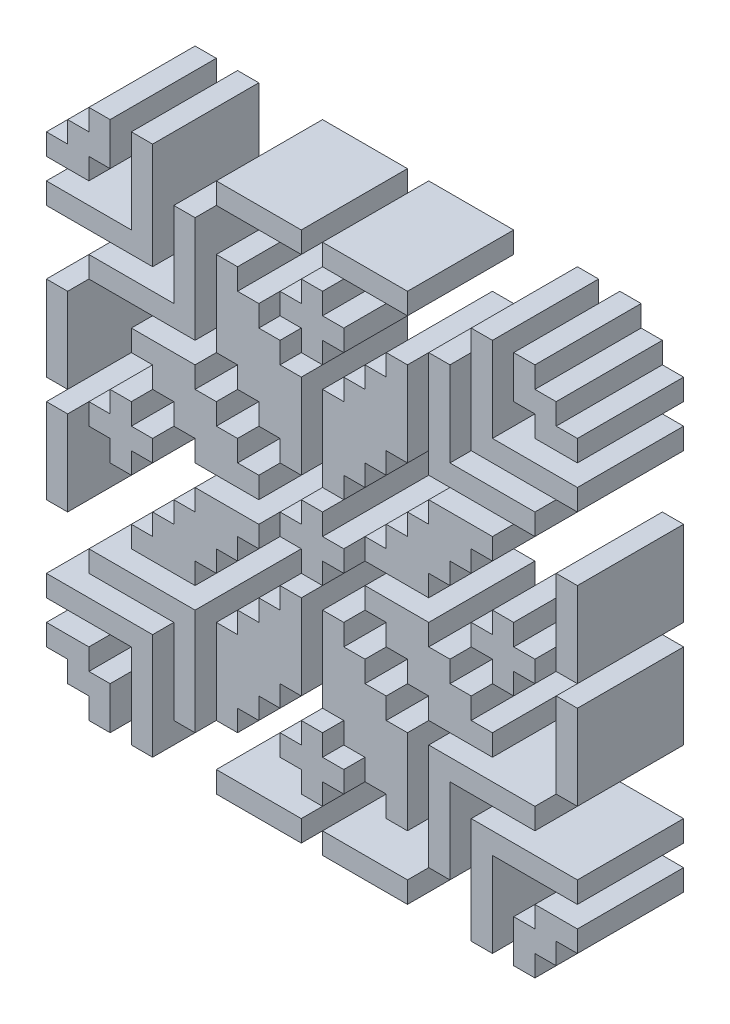
SolidWorks part; units mm, degrees
ref_plane "Спереди" through (0, 0, 0) normal (0, 0, 1) x (1, 0, 0)
ref_plane "Сверху" through (0, 0, 0) normal (0, 1, 0) x (1, 0, 0)
ref_plane "Справа" through (0, 0, 0) normal (1, 0, 0) x (0, 0, -1)
sketch "Эскиз1" plane through (0, 0, 0) normal (0, 0, 1) x (1, 0, 0)
  line L1 (-13.5, 13.5) -> (13.5, 13.5)
  line L2 (-13.5, 13.5) -> (-13.5, -13.5)
  line L3 (-13.5, -13.5) -> (13.5, -13.5)
  line L4 (13.5, 13.5) -> (13.5, -13.5)
  line L5 (-13.5, 13.5) -> (13.5, -13.5) construction
  line L6 (-13.5, -13.5) -> (13.5, 13.5) construction
  point P0 (0, 0)
  dimension "D1" = 27
  dimension "D2" = 27
extrude "Бобышка-Вытянуть1" [suppressed] add sketch "Эскиз1" along normal blind 3
sketch "Эскиз2" [suppressed] plane through (0, 0, 0) normal (0, 0, 1) x (1, 0, 0)
  line L0 (0, 0) -> (-13.5, 0) construction
  line L1 (-13.5, 13.5) -> (-13.5, -13.5) construction
  line L2 (0, 0) -> (0, -13.5) construction
  line L3 (-13.5, -13.5) -> (13.5, -13.5) construction
  line L4 (-0.5, -0.5) -> (-1.5, -0.5)
  line L5 (0.5, -1.5) -> (-0.5, -1.5)
  line L6 (0.5, -1.5) -> (0.5, -0.5)
  line L7 (0.5, 1.5) -> (-0.5, 1.5)
  line L8 (-0.5, -1.5) -> (-0.5, -0.5)
  line L9 (0.5, -1.5) -> (-0.5, 1.5) construction
  line L10 (0.5, 1.5) -> (-0.5, -1.5) construction
  line L11 (1.5, -0.5) -> (0.5, -0.5)
  line L12 (1.5, -0.5) -> (1.5, 0.5)
  line L13 (1.5, 0.5) -> (0.5, 0.5)
  line L14 (-1.5, -0.5) -> (-1.5, 0.5)
  line L15 (1.5, -0.5) -> (-1.5, 0.5) construction
  line L16 (1.5, 0.5) -> (-1.5, -0.5) construction
  line L17 (0.5, 0.5) -> (0.5, 1.5)
  line L18 (-0.5, 0.5) -> (-1.5, 0.5)
  line L19 (-0.5, 0.5) -> (-0.5, 1.5)
  line L20 (0, -9) -> (3.8771, -9) construction
  line L21 (1.5, 8.5) -> (-1.5, 9.5) construction
  line L22 (-0.5, -9.5) -> (-1.5, -9.5)
  line L23 (0.5, -10.5) -> (-0.5, -10.5)
  line L24 (0.5, -10.5) -> (0.5, -9.5)
  line L25 (0.5, -7.5) -> (-0.5, -7.5)
  line L26 (-0.5, -10.5) -> (-0.5, -9.5)
  line L27 (0.5, -10.5) -> (-0.5, -7.5) construction
  line L28 (0.5, -7.5) -> (-0.5, -10.5) construction
  line L29 (1.5, -9.5) -> (0.5, -9.5)
  line L30 (1.5, -9.5) -> (1.5, -8.5)
  line L31 (1.5, -8.5) -> (0.5, -8.5)
  line L32 (-1.5, -9.5) -> (-1.5, -8.5)
  line L33 (1.5, -9.5) -> (-1.5, -8.5) construction
  line L34 (1.5, -8.5) -> (-1.5, -9.5) construction
  line L35 (0.5, -8.5) -> (0.5, -7.5)
  line L36 (-0.5, -8.5) -> (-1.5, -8.5)
  line L37 (-0.5, -8.5) -> (-0.5, -7.5)
  line L38 (1.5, 9.5) -> (-1.5, 8.5) construction
  line L39 (0.5, 7.5) -> (-0.5, 10.5) construction
  line L40 (0.5, 10.5) -> (-0.5, 7.5) construction
  line L41 (-0.5, 8.5) -> (-0.5, 7.5)
  line L42 (-0.5, 8.5) -> (-1.5, 8.5)
  line L43 (0.5, 8.5) -> (0.5, 7.5)
  line L44 (-1.5, 9.5) -> (-1.5, 8.5)
  line L45 (1.5, 8.5) -> (0.5, 8.5)
  line L46 (1.5, 9.5) -> (1.5, 8.5)
  line L47 (1.5, 9.5) -> (0.5, 9.5)
  line L48 (-0.5, 10.5) -> (-0.5, 9.5)
  line L49 (0.5, 7.5) -> (-0.5, 7.5)
  line L50 (0.5, 10.5) -> (0.5, 9.5)
  line L51 (0.5, 10.5) -> (-0.5, 10.5)
  line L52 (-0.5, 9.5) -> (-1.5, 9.5)
  line L53 (2.5, -0.5) -> (5.5, -0.5)
  line L54 (5.5, -0.5) -> (5.5, -1.5)
  line L55 (5.5, -1.5) -> (6.5, -1.5)
  line L56 (6.5, -1.5) -> (6.5, -2.5)
  line L57 (6.5, -2.5) -> (7.5, -2.5)
  line L58 (7.5, -2.5) -> (7.5, -3.5)
  line L59 (7.5, -3.5) -> (8.5, -3.5)
  line L60 (8.5, -3.5) -> (8.5, -4.5)
  line L61 (8.5, -4.5) -> (5.5, -4.5)
  line L62 (5.5, -4.5) -> (5.5, -3.5)
  line L63 (5.5, -3.5) -> (4.5, -3.5)
  line L64 (4.5, -3.5) -> (4.5, -2.5)
  line L65 (4.5, -2.5) -> (3.5, -2.5)
  line L66 (3.5, -2.5) -> (3.5, -1.5)
  line L67 (3.5, -1.5) -> (2.5, -1.5)
  line L68 (2.5, -1.5) -> (2.5, -0.5)
  line L69 (5.5, -1.5) -> (5.5, -3.5) construction
  line L70 (5.5, -10.5) -> (5.5, -5.5)
  line L71 (5.5, -5.5) -> (10.5, -5.5)
  line L72 (10.5, -5.5) -> (10.5, -6.5)
  line L73 (10.5, -6.5) -> (6.5, -6.5)
  line L74 (6.5, -6.5) -> (6.5, -10.5)
  line L75 (6.5, -10.5) -> (5.5, -10.5)
  line L76 (5.5, -4.5) -> (5.5, -5.5) construction
  line L77 (8.5, -12.5) -> (7.5, -12.5)
  line L78 (7.5, -12.5) -> (7.5, -7.5)
  line L79 (7.5, -7.5) -> (12.5, -7.5)
  line L80 (12.5, -7.5) -> (12.5, -8.5)
  line L81 (12.5, -8.5) -> (8.5, -8.5)
  line L82 (8.5, -8.5) -> (8.5, -12.5)
  line L83 (9.5, -12.5) -> (9.5, -10.5)
  line L84 (9.5, -10.5) -> (10.5, -10.5)
  line L85 (10.5, -10.5) -> (10.5, -9.5)
  line L86 (10.5, -9.5) -> (12.5, -9.5)
  line L87 (12.5, -9.5) -> (12.5, -10.5)
  line L88 (12.5, -10.5) -> (11.5, -10.5)
  line L89 (11.5, -10.5) -> (11.5, -11.5)
  line L90 (11.5, -11.5) -> (10.5, -11.5)
  line L91 (10.5, -11.5) -> (10.5, -12.5)
  line L92 (10.5, -12.5) -> (9.5, -12.5)
  line L93 (0.5, -2.5) -> (0.5, -6.5)
  line L94 (0.5, -6.5) -> (1.5, -6.5)
  line L95 (1.5, -6.5) -> (1.5, -7.5)
  line L96 (1.5, -7.5) -> (2.5, -7.5)
  line L97 (2.5, -7.5) -> (2.5, -8.5)
  line L98 (2.5, -8.5) -> (3.5, -8.5)
  line L99 (3.5, -8.5) -> (3.5, -9.5)
  line L100 (3.5, -9.5) -> (4.5, -9.5)
  line L103 (4.5, -9.5) -> (4.5, -5.5)
  line L106 (4.5, -5.5) -> (3.5, -5.5)
  line L107 (3.5, -5.5) -> (3.5, -4.5)
  line L108 (3.5, -4.5) -> (2.5, -4.5)
  line L109 (2.5, -4.5) -> (2.5, -3.5)
  line L110 (2.5, -3.5) -> (1.5, -3.5)
  line L111 (1.5, -3.5) -> (1.5, -2.5)
  line L112 (1.5, -2.5) -> (0.5, -2.5)
  line L113 (0.5, -6.5) -> (0.5, -7.5) construction
  line L114 (1.5, -3.5) -> (1.5, -6.5) construction
  line L115 (2.5, -4.5) -> (2.5, -7.5) construction
  line L116 (0.5, -10.5) -> (0.5, -11.5) construction
  line L117 (4.5, -12.5) -> (0.5, -12.5)
  line L118 (4.5, -12.5) -> (4.5, -11.5)
  line L119 (4.5, -11.5) -> (0.5, -11.5)
  line L120 (0.5, -12.5) -> (0.5, -11.5)
  line L121 (9, 0) -> (17.8062, 0) construction
  line L122 (9, 0) -> (9, -6.8908) construction
  line L123 (8.5, -0.5) -> (7.5, -0.5)
  line L124 (9.5, -1.5) -> (8.5, -1.5)
  line L125 (9.5, -1.5) -> (9.5, -0.5)
  line L126 (9.5, 1.5) -> (8.5, 1.5)
  line L127 (8.5, -1.5) -> (8.5, -0.5)
  line L128 (9.5, -1.5) -> (8.5, 1.5) construction
  line L129 (9.5, 1.5) -> (8.5, -1.5) construction
  line L130 (10.5, -0.5) -> (9.5, -0.5)
  line L131 (10.5, -0.5) -> (10.5, 0.5)
  line L132 (10.5, 0.5) -> (9.5, 0.5)
  line L133 (7.5, -0.5) -> (7.5, 0.5)
  line L134 (10.5, -0.5) -> (7.5, 0.5) construction
  line L135 (10.5, 0.5) -> (7.5, -0.5) construction
  line L136 (9.5, 0.5) -> (9.5, 1.5)
  line L137 (8.5, 0.5) -> (7.5, 0.5)
  line L138 (8.5, 0.5) -> (8.5, 1.5)
  line L139 (-9, 0) -> (0, 0) construction
  line L140 (-9, 0) -> (-9, -7.0023) construction
  line L141 (-9.5, -0.5) -> (-10.5, -0.5)
  line L142 (-8.5, -1.5) -> (-9.5, -1.5)
  line L143 (-8.5, -1.5) -> (-8.5, -0.5)
  line L144 (-8.5, 1.5) -> (-9.5, 1.5)
  line L145 (-9.5, -1.5) -> (-9.5, -0.5)
  line L146 (-8.5, -1.5) -> (-9.5, 1.5) construction
  line L147 (-8.5, 1.5) -> (-9.5, -1.5) construction
  line L148 (-7.5, -0.5) -> (-8.5, -0.5)
  line L149 (-7.5, -0.5) -> (-7.5, 0.5)
  line L150 (-7.5, 0.5) -> (-8.5, 0.5)
  line L151 (-10.5, -0.5) -> (-10.5, 0.5)
  line L152 (-7.5, -0.5) -> (-10.5, 0.5) construction
  line L153 (-7.5, 0.5) -> (-10.5, -0.5) construction
  line L154 (-8.5, 0.5) -> (-8.5, 1.5)
  line L155 (-9.5, 0.5) -> (-10.5, 0.5)
  line L156 (-9.5, 0.5) -> (-9.5, 1.5)
  line L157 (-4.5, -11.5) -> (-0.5, -11.5)
  line L158 (-0.5, -12.5) -> (-0.5, -11.5)
  line L159 (-4.5, -12.5) -> (-0.5, -12.5)
  line L160 (-4.5, -12.5) -> (-4.5, -11.5)
  line L161 (-10.5, -12.5) -> (-9.5, -12.5)
  line L162 (-10.5, -11.5) -> (-10.5, -12.5)
  line L163 (-11.5, -11.5) -> (-10.5, -11.5)
  line L164 (-11.5, -10.5) -> (-11.5, -11.5)
  line L165 (-12.5, -10.5) -> (-11.5, -10.5)
  line L166 (-12.5, -9.5) -> (-12.5, -10.5)
  line L167 (-10.5, -9.5) -> (-12.5, -9.5)
  line L168 (-10.5, -10.5) -> (-10.5, -9.5)
  line L169 (-9.5, -10.5) -> (-10.5, -10.5)
  line L170 (-9.5, -12.5) -> (-9.5, -10.5)
  line L171 (-12.5, -8.5) -> (-8.5, -8.5)
  line L172 (-12.5, -7.5) -> (-12.5, -8.5)
  line L173 (-7.5, -7.5) -> (-12.5, -7.5)
  line L174 (-7.5, -12.5) -> (-7.5, -7.5)
  line L175 (-8.5, -12.5) -> (-7.5, -12.5)
  line L176 (-8.5, -8.5) -> (-8.5, -12.5)
  line L177 (-6.5, -6.5) -> (-6.5, -10.5)
  line L178 (-10.5, -6.5) -> (-6.5, -6.5)
  line L179 (-10.5, -5.5) -> (-10.5, -6.5)
  line L180 (-5.5, -5.5) -> (-10.5, -5.5)
  line L181 (-5.5, -10.5) -> (-5.5, -5.5)
  line L182 (-6.5, -10.5) -> (-5.5, -10.5)
  line L183 (-3.5, -1.5) -> (-2.5, -1.5)
  line L184 (-3.5, -2.5) -> (-3.5, -1.5)
  line L185 (-4.5, -2.5) -> (-3.5, -2.5)
  line L186 (-4.5, -3.5) -> (-4.5, -2.5)
  line L187 (-5.5, -3.5) -> (-4.5, -3.5)
  line L188 (-5.5, -4.5) -> (-5.5, -3.5)
  line L189 (-8.5, -4.5) -> (-5.5, -4.5)
  line L190 (-8.5, -3.5) -> (-8.5, -4.5)
  line L191 (-7.5, -3.5) -> (-8.5, -3.5)
  line L192 (-7.5, -2.5) -> (-7.5, -3.5)
  line L193 (-6.5, -2.5) -> (-7.5, -2.5)
  line L194 (-6.5, -1.5) -> (-6.5, -2.5)
  line L195 (-5.5, -1.5) -> (-6.5, -1.5)
  line L196 (-5.5, -0.5) -> (-5.5, -1.5)
  line L197 (-2.5, -0.5) -> (-5.5, -0.5)
  line L198 (-2.5, -1.5) -> (-2.5, -0.5)
  line L199 (-3.5, -9.5) -> (-4.5, -9.5)
  line L200 (-3.5, -8.5) -> (-3.5, -9.5)
  line L201 (-2.5, -8.5) -> (-3.5, -8.5)
  line L202 (-2.5, -7.5) -> (-2.5, -8.5)
  line L203 (-1.5, -7.5) -> (-2.5, -7.5)
  line L204 (-1.5, -6.5) -> (-1.5, -7.5)
  line L205 (-0.5, -6.5) -> (-1.5, -6.5)
  line L206 (-0.5, -2.5) -> (-0.5, -6.5)
  line L207 (-1.5, -2.5) -> (-0.5, -2.5)
  line L208 (-1.5, -3.5) -> (-1.5, -2.5)
  line L209 (-2.5, -3.5) -> (-1.5, -3.5)
  line L210 (-2.5, -4.5) -> (-2.5, -3.5)
  line L211 (-3.5, -4.5) -> (-2.5, -4.5)
  line L212 (-3.5, -5.5) -> (-3.5, -4.5)
  line L213 (-4.5, -5.5) -> (-3.5, -5.5)
  line L214 (-4.5, -9.5) -> (-4.5, -5.5)
  line L215 (8.5, -4.5) -> (11.5, -4.5) construction
  line L216 (12.5, -0.5) -> (11.5, -0.5)
  line L217 (12.5, -0.5) -> (12.5, -4.5)
  line L218 (12.5, -4.5) -> (11.5, -4.5)
  line L219 (11.5, -0.5) -> (11.5, -4.5)
  line L220 (12.5, -4.5) -> (12.5, -7.5) construction
  line L221 (-12.5, -4.5) -> (-11.5, -4.5)
  line L222 (-11.5, -0.5) -> (-11.5, -4.5)
  line L223 (-12.5, -0.5) -> (-11.5, -0.5)
  line L224 (-12.5, -0.5) -> (-12.5, -4.5)
  line L225 (-10.5, 11.5) -> (-10.5, 12.5)
  line L226 (-11.5, 11.5) -> (-10.5, 11.5)
  line L227 (-11.5, 10.5) -> (-11.5, 11.5)
  line L228 (-12.5, 10.5) -> (-11.5, 10.5)
  line L229 (-12.5, 9.5) -> (-12.5, 10.5)
  line L230 (-10.5, 9.5) -> (-12.5, 9.5)
  line L231 (-10.5, 10.5) -> (-10.5, 9.5)
  line L232 (-9.5, 10.5) -> (-10.5, 10.5)
  line L233 (-9.5, 12.5) -> (-9.5, 10.5)
  line L234 (-10.5, 12.5) -> (-9.5, 12.5)
  line L235 (-12.5, 7.5) -> (-12.5, 8.5)
  line L236 (-7.5, 7.5) -> (-12.5, 7.5)
  line L237 (-7.5, 12.5) -> (-7.5, 7.5)
  line L238 (-8.5, 12.5) -> (-7.5, 12.5)
  line L239 (-8.5, 8.5) -> (-8.5, 12.5)
  line L240 (-12.5, 8.5) -> (-8.5, 8.5)
  line L241 (-10.5, 6.5) -> (-6.5, 6.5)
  line L242 (-10.5, 5.5) -> (-10.5, 6.5)
  line L243 (-5.5, 5.5) -> (-10.5, 5.5)
  line L244 (-5.5, 10.5) -> (-5.5, 5.5)
  line L245 (-6.5, 10.5) -> (-5.5, 10.5)
  line L246 (-6.5, 6.5) -> (-6.5, 10.5)
  line L247 (-12.5, 0.5) -> (-12.5, 4.5)
  line L248 (-12.5, 0.5) -> (-11.5, 0.5)
  line L249 (-11.5, 0.5) -> (-11.5, 4.5)
  line L250 (-12.5, 4.5) -> (-11.5, 4.5)
  line L251 (-3.5, 2.5) -> (-3.5, 1.5)
  line L252 (-4.5, 2.5) -> (-3.5, 2.5)
  line L253 (-4.5, 3.5) -> (-4.5, 2.5)
  line L254 (-5.5, 3.5) -> (-4.5, 3.5)
  line L255 (-5.5, 4.5) -> (-5.5, 3.5)
  line L256 (-8.5, 4.5) -> (-5.5, 4.5)
  line L257 (-8.5, 3.5) -> (-8.5, 4.5)
  line L258 (-7.5, 3.5) -> (-8.5, 3.5)
  line L259 (-7.5, 2.5) -> (-7.5, 3.5)
  line L260 (-6.5, 2.5) -> (-7.5, 2.5)
  line L261 (-6.5, 1.5) -> (-6.5, 2.5)
  line L262 (-5.5, 1.5) -> (-6.5, 1.5)
  line L263 (-5.5, 0.5) -> (-5.5, 1.5)
  line L264 (-2.5, 0.5) -> (-5.5, 0.5)
  line L265 (-2.5, 1.5) -> (-2.5, 0.5)
  line L266 (-3.5, 1.5) -> (-2.5, 1.5)
  line L267 (-3.5, 8.5) -> (-3.5, 9.5)
  line L268 (-2.5, 8.5) -> (-3.5, 8.5)
  line L269 (-2.5, 7.5) -> (-2.5, 8.5)
  line L270 (-1.5, 7.5) -> (-2.5, 7.5)
  line L271 (-1.5, 6.5) -> (-1.5, 7.5)
  line L272 (-0.5, 6.5) -> (-1.5, 6.5)
  line L273 (-0.5, 2.5) -> (-0.5, 6.5)
  line L274 (-1.5, 2.5) -> (-0.5, 2.5)
  line L275 (-1.5, 3.5) -> (-1.5, 2.5)
  line L276 (-2.5, 3.5) -> (-1.5, 3.5)
  line L277 (-2.5, 4.5) -> (-2.5, 3.5)
  line L278 (-3.5, 4.5) -> (-2.5, 4.5)
  line L279 (-3.5, 5.5) -> (-3.5, 4.5)
  line L280 (-4.5, 5.5) -> (-3.5, 5.5)
  line L281 (-4.5, 9.5) -> (-4.5, 5.5)
  line L282 (-3.5, 9.5) -> (-4.5, 9.5)
  line L283 (-4.5, 12.5) -> (-4.5, 11.5)
  line L284 (-4.5, 12.5) -> (-0.5, 12.5)
  line L285 (-0.5, 12.5) -> (-0.5, 11.5)
  line L286 (-4.5, 11.5) -> (-0.5, 11.5)
  line L287 (4.5, 11.5) -> (0.5, 11.5)
  line L288 (0.5, 12.5) -> (0.5, 11.5)
  line L289 (4.5, 12.5) -> (0.5, 12.5)
  line L290 (4.5, 12.5) -> (4.5, 11.5)
  line L291 (3.5, 9.5) -> (4.5, 9.5)
  line L292 (3.5, 8.5) -> (3.5, 9.5)
  line L293 (2.5, 8.5) -> (3.5, 8.5)
  line L294 (2.5, 7.5) -> (2.5, 8.5)
  line L295 (1.5, 7.5) -> (2.5, 7.5)
  line L296 (1.5, 6.5) -> (1.5, 7.5)
  line L297 (0.5, 6.5) -> (1.5, 6.5)
  line L298 (0.5, 2.5) -> (0.5, 6.5)
  line L299 (1.5, 2.5) -> (0.5, 2.5)
  line L300 (1.5, 3.5) -> (1.5, 2.5)
  line L301 (2.5, 3.5) -> (1.5, 3.5)
  line L302 (2.5, 4.5) -> (2.5, 3.5)
  line L303 (3.5, 4.5) -> (2.5, 4.5)
  line L304 (3.5, 5.5) -> (3.5, 4.5)
  line L305 (4.5, 5.5) -> (3.5, 5.5)
  line L306 (4.5, 9.5) -> (4.5, 5.5)
  line L307 (10.5, 12.5) -> (9.5, 12.5)
  line L308 (10.5, 11.5) -> (10.5, 12.5)
  line L309 (11.5, 11.5) -> (10.5, 11.5)
  line L310 (11.5, 10.5) -> (11.5, 11.5)
  line L311 (12.5, 10.5) -> (11.5, 10.5)
  line L312 (12.5, 9.5) -> (12.5, 10.5)
  line L313 (10.5, 9.5) -> (12.5, 9.5)
  line L314 (10.5, 10.5) -> (10.5, 9.5)
  line L315 (9.5, 10.5) -> (10.5, 10.5)
  line L316 (9.5, 12.5) -> (9.5, 10.5)
  line L317 (12.5, 8.5) -> (8.5, 8.5)
  line L318 (12.5, 7.5) -> (12.5, 8.5)
  line L319 (7.5, 7.5) -> (12.5, 7.5)
  line L320 (7.5, 12.5) -> (7.5, 7.5)
  line L321 (8.5, 12.5) -> (7.5, 12.5)
  line L322 (8.5, 8.5) -> (8.5, 12.5)
  line L323 (6.5, 6.5) -> (6.5, 10.5)
  line L324 (10.5, 6.5) -> (6.5, 6.5)
  line L325 (10.5, 5.5) -> (10.5, 6.5)
  line L326 (5.5, 5.5) -> (10.5, 5.5)
  line L327 (5.5, 10.5) -> (5.5, 5.5)
  line L328 (6.5, 10.5) -> (5.5, 10.5)
  line L329 (3.5, 1.5) -> (2.5, 1.5)
  line L330 (3.5, 2.5) -> (3.5, 1.5)
  line L331 (4.5, 2.5) -> (3.5, 2.5)
  line L332 (4.5, 3.5) -> (4.5, 2.5)
  line L333 (5.5, 3.5) -> (4.5, 3.5)
  line L334 (5.5, 4.5) -> (5.5, 3.5)
  line L335 (8.5, 4.5) -> (5.5, 4.5)
  line L336 (8.5, 3.5) -> (8.5, 4.5)
  line L337 (7.5, 3.5) -> (8.5, 3.5)
  line L338 (7.5, 2.5) -> (7.5, 3.5)
  line L339 (6.5, 2.5) -> (7.5, 2.5)
  line L340 (6.5, 1.5) -> (6.5, 2.5)
  line L341 (5.5, 1.5) -> (6.5, 1.5)
  line L342 (5.5, 0.5) -> (5.5, 1.5)
  line L343 (2.5, 0.5) -> (5.5, 0.5)
  line L344 (2.5, 1.5) -> (2.5, 0.5)
  line L345 (12.5, 4.5) -> (11.5, 4.5)
  line L346 (11.5, 0.5) -> (11.5, 4.5)
  line L347 (12.5, 0.5) -> (11.5, 0.5)
  line L348 (12.5, 0.5) -> (12.5, 4.5)
  point P65 (5.5, -1.5)
  dimension "D1" = 3
  dimension "D2" = 3
  dimension "D3" = 1
  dimension "D4" = 1
  dimension "D5" = 3
  dimension "D6" = 3
  dimension "D7" = 1
  dimension "D8" = 1
  dimension "D9" = 9
  dimension "D10" = 1
  dimension "D11" = 1
  dimension "D12" = 1
  dimension "D13" = 1
  dimension "D14" = 1
  dimension "D15" = 1
  dimension "D16" = 1
  dimension "D17" = 1
  dimension "D18" = 1
  dimension "D19" = 1
  dimension "D20" = 1
  dimension "D21" = 1
  dimension "D22" = 1
  dimension "D23" = 0.5
  dimension "D24" = 1
  dimension "D25" = 1
  dimension "D26" = 1
  dimension "D27" = 5
  dimension "D28" = 5
  dimension "D29" = 1
  dimension "D30" = 5
  dimension "D31" = 5
  dimension "D32" = 1
  dimension "D33" = 1
  dimension "D34" = 1
  dimension "D35" = 1
  dimension "D36" = 2
  dimension "D37" = 1
  dimension "D38" = 1
  dimension "D39" = 1
  dimension "D40" = 1
  dimension "D41" = 1
  dimension "D42" = 1
  dimension "D43" = 1
  dimension "D44" = 1
  dimension "D45" = 1
  dimension "D46" = 1
  dimension "D47" = 1
  dimension "D48" = 1
  dimension "D49" = 1
  dimension "D50" = 1
  dimension "D51" = 1
  dimension "D52" = 1
  dimension "D53" = 1
  dimension "D54" = 4
  dimension "D55" = 4
  dimension "D56" = 1
  dimension "D57" = 1
  dimension "D58" = 1
  dimension "D59" = 1
  dimension "D60" = 1
  dimension "D61" = 1
  dimension "D62" = 3
  dimension "D63" = 3
  dimension "D64" = 1
  dimension "D65" = 1
  dimension "D66" = 3
  dimension "D67" = 3
  dimension "D68" = 1
  dimension "D69" = 1
  dimension "D70" = 9
  dimension "D71" = 9
  dimension "D72" = 1
  dimension "D73" = 4
extrude "Бобышка-Вытянуть2" [suppressed] add sketch "Эскиз2" along normal blind 10
sketch "Эскиз3" plane through (0, 0, 0) normal (0, 0, 1) x (1, 0, 0)
  line L0 (0, 0) -> (0, 54.9561) construction
  line L1 (0, 0) -> (20.3527, 0) construction
  line L2 (0, 0) -> (0, -2.9834) construction
  line L3 (-0.5, -0.5) -> (-1.5, -0.5)
  line L4 (0.5, -1.5) -> (-0.5, -1.5)
  line L5 (0.5, -1.5) -> (0.5, -0.5)
  line L6 (0.5, 1.5) -> (-0.5, 1.5)
  line L7 (-0.5, -1.5) -> (-0.5, -0.5)
  line L8 (0.5, -1.5) -> (-0.5, 1.5) construction
  line L9 (0.5, 1.5) -> (-0.5, -1.5) construction
  line L10 (1.5, -0.5) -> (0.5, -0.5)
  line L11 (1.5, -0.5) -> (1.5, 0.5)
  line L12 (1.5, 0.5) -> (0.5, 0.5)
  line L13 (-1.5, -0.5) -> (-1.5, 0.5)
  line L14 (1.5, -0.5) -> (-1.5, 0.5) construction
  line L15 (1.5, 0.5) -> (-1.5, -0.5) construction
  line L16 (0.5, 0.5) -> (0.5, 1.5)
  line L17 (-0.5, 0.5) -> (-1.5, 0.5)
  line L18 (-0.5, 0.5) -> (-0.5, 1.5)
  line L19 (0, -9) -> (37.7298, -9) construction
  line L20 (1.5, 8.5) -> (-1.5, 9.5) construction
  line L21 (-0.5, -9.5) -> (-1.5, -9.5)
  line L22 (0.5, -10.5) -> (-0.5, -10.5)
  line L23 (0.5, -10.5) -> (0.5, -9.5)
  line L24 (0.5, -7.5) -> (-0.5, -7.5)
  line L25 (-0.5, -10.5) -> (-0.5, -9.5)
  line L26 (0.5, -10.5) -> (-0.5, -7.5) construction
  line L27 (0.5, -7.5) -> (-0.5, -10.5) construction
  line L28 (1.5, -9.5) -> (0.5, -9.5)
  line L29 (1.5, -9.5) -> (1.5, -8.5)
  line L30 (1.5, -8.5) -> (0.5, -8.5)
  line L31 (-1.5, -9.5) -> (-1.5, -8.5)
  line L32 (1.5, -9.5) -> (-1.5, -8.5) construction
  line L33 (1.5, -8.5) -> (-1.5, -9.5) construction
  line L34 (0.5, -8.5) -> (0.5, -7.5)
  line L35 (-0.5, -8.5) -> (-1.5, -8.5)
  line L36 (-0.5, -8.5) -> (-0.5, -7.5)
  line L37 (1.5, 9.5) -> (-1.5, 8.5) construction
  line L38 (0.5, 7.5) -> (-0.5, 10.5) construction
  line L39 (0.5, 10.5) -> (-0.5, 7.5) construction
  line L40 (-0.5, 8.5) -> (-0.5, 7.5)
  line L41 (-0.5, 8.5) -> (-1.5, 8.5)
  line L42 (0.5, 8.5) -> (0.5, 7.5)
  line L43 (-1.5, 9.5) -> (-1.5, 8.5)
  line L44 (1.5, 8.5) -> (0.5, 8.5)
  line L45 (1.5, 9.5) -> (1.5, 8.5)
  line L46 (1.5, 9.5) -> (0.5, 9.5)
  line L47 (-0.5, 10.5) -> (-0.5, 9.5)
  line L48 (0.5, 7.5) -> (-0.5, 7.5)
  line L49 (0.5, 10.5) -> (0.5, 9.5)
  line L50 (0.5, 10.5) -> (-0.5, 10.5)
  line L51 (-0.5, 9.5) -> (-1.5, 9.5)
  line L52 (2.5, -0.5) -> (5.5, -0.5)
  line L53 (5.5, -0.5) -> (5.5, -1.5)
  line L54 (5.5, -1.5) -> (6.5, -1.5)
  line L55 (6.5, -1.5) -> (6.5, -2.5)
  line L56 (6.5, -2.5) -> (7.5, -2.5)
  line L57 (7.5, -2.5) -> (7.5, -3.5)
  line L58 (7.5, -3.5) -> (8.5, -3.5)
  line L59 (8.5, -3.5) -> (8.5, -4.5)
  line L60 (8.5, -4.5) -> (5.5, -4.5)
  line L61 (5.5, -4.5) -> (5.5, -3.5)
  line L62 (5.5, -3.5) -> (4.5, -3.5)
  line L63 (4.5, -3.5) -> (4.5, -2.5)
  line L64 (4.5, -2.5) -> (3.5, -2.5)
  line L65 (3.5, -2.5) -> (3.5, -1.5)
  line L66 (3.5, -1.5) -> (2.5, -1.5)
  line L67 (2.5, -1.5) -> (2.5, -0.5)
  line L68 (5.5, -1.5) -> (5.5, -3.5) construction
  line L69 (5.5, -10.5) -> (5.5, -5.5)
  line L70 (5.5, -5.5) -> (10.5, -5.5)
  line L71 (10.5, -5.5) -> (10.5, -6.5)
  line L72 (10.5, -6.5) -> (6.5, -6.5)
  line L73 (6.5, -6.5) -> (6.5, -10.5)
  line L74 (6.5, -10.5) -> (5.5, -10.5)
  line L75 (5.5, -4.5) -> (5.5, -5.5) construction
  line L76 (8.5, -12.5) -> (7.5, -12.5)
  line L77 (7.5, -12.5) -> (7.5, -7.5)
  line L78 (7.5, -7.5) -> (12.5, -7.5)
  line L79 (12.5, -7.5) -> (12.5, -8.5)
  line L80 (12.5, -8.5) -> (8.5, -8.5)
  line L81 (8.5, -8.5) -> (8.5, -12.5)
  line L82 (9.5, -12.5) -> (9.5, -10.5)
  line L83 (9.5, -10.5) -> (10.5, -10.5)
  line L84 (10.5, -10.5) -> (10.5, -9.5)
  line L85 (10.5, -9.5) -> (12.5, -9.5)
  line L86 (12.5, -9.5) -> (12.5, -10.5)
  line L87 (12.5, -10.5) -> (11.5, -10.5)
  line L88 (11.5, -10.5) -> (11.5, -11.5)
  line L89 (11.5, -11.5) -> (10.5, -11.5)
  line L90 (10.5, -11.5) -> (10.5, -12.5)
  line L91 (10.5, -12.5) -> (9.5, -12.5)
  line L92 (0.5, -2.5) -> (0.5, -6.5)
  line L93 (0.5, -6.5) -> (1.5, -6.5)
  line L94 (1.5, -6.5) -> (1.5, -7.5)
  line L95 (1.5, -7.5) -> (2.5, -7.5)
  line L96 (2.5, -7.5) -> (2.5, -8.5)
  line L97 (2.5, -8.5) -> (3.5, -8.5)
  line L98 (3.5, -8.5) -> (3.5, -9.5)
  line L99 (3.5, -9.5) -> (4.5, -9.5)
  line L100 (4.5, -9.5) -> (4.5, -5.5)
  line L101 (4.5, -5.5) -> (3.5, -5.5)
  line L102 (3.5, -5.5) -> (3.5, -4.5)
  line L103 (3.5, -4.5) -> (2.5, -4.5)
  line L104 (2.5, -4.5) -> (2.5, -3.5)
  line L105 (2.5, -3.5) -> (1.5, -3.5)
  line L106 (1.5, -3.5) -> (1.5, -2.5)
  line L107 (1.5, -2.5) -> (0.5, -2.5)
  line L108 (0.5, -6.5) -> (0.5, -7.5) construction
  line L109 (1.5, -3.5) -> (1.5, -6.5) construction
  line L110 (2.5, -4.5) -> (2.5, -7.5) construction
  line L111 (0.5, -10.5) -> (0.5, -11.5) construction
  line L112 (4.5, -12.5) -> (0.5, -12.5)
  line L113 (4.5, -12.5) -> (4.5, -11.5)
  line L114 (4.5, -11.5) -> (0.5, -11.5)
  line L115 (0.5, -12.5) -> (0.5, -11.5)
  line L116 (9, 0) -> (51.6588, 0) construction
  line L117 (9, 0) -> (9, 3.6258) construction
  line L118 (8.5, -0.5) -> (7.5, -0.5)
  line L119 (9.5, -1.5) -> (8.5, -1.5)
  line L120 (9.5, -1.5) -> (9.5, -0.5)
  line L121 (9.5, 1.5) -> (8.5, 1.5)
  line L122 (8.5, -1.5) -> (8.5, -0.5)
  line L123 (9.5, -1.5) -> (8.5, 1.5) construction
  line L124 (9.5, 1.5) -> (8.5, -1.5) construction
  line L125 (10.5, -0.5) -> (9.5, -0.5)
  line L126 (10.5, -0.5) -> (10.5, 0.5)
  line L127 (10.5, 0.5) -> (9.5, 0.5)
  line L128 (7.5, -0.5) -> (7.5, 0.5)
  line L129 (10.5, -0.5) -> (7.5, 0.5) construction
  line L130 (10.5, 0.5) -> (7.5, -0.5) construction
  line L131 (9.5, 0.5) -> (9.5, 1.5)
  line L132 (8.5, 0.5) -> (7.5, 0.5)
  line L133 (8.5, 0.5) -> (8.5, 1.5)
  line L134 (-9, 0) -> (0, 0) construction
  line L135 (-9, 0) -> (-9, 3.5144) construction
  line L136 (-9.5, -0.5) -> (-10.5, -0.5)
  line L137 (-8.5, -1.5) -> (-9.5, -1.5)
  line L138 (-8.5, -1.5) -> (-8.5, -0.5)
  line L139 (-8.5, 1.5) -> (-9.5, 1.5)
  line L140 (-9.5, -1.5) -> (-9.5, -0.5)
  line L141 (-8.5, -1.5) -> (-9.5, 1.5) construction
  line L142 (-8.5, 1.5) -> (-9.5, -1.5) construction
  line L143 (-7.5, -0.5) -> (-8.5, -0.5)
  line L144 (-7.5, -0.5) -> (-7.5, 0.5)
  line L145 (-7.5, 0.5) -> (-8.5, 0.5)
  line L146 (-10.5, -0.5) -> (-10.5, 0.5)
  line L147 (-7.5, -0.5) -> (-10.5, 0.5) construction
  line L148 (-7.5, 0.5) -> (-10.5, -0.5) construction
  line L149 (-8.5, 0.5) -> (-8.5, 1.5)
  line L150 (-9.5, 0.5) -> (-10.5, 0.5)
  line L151 (-9.5, 0.5) -> (-9.5, 1.5)
  line L152 (-4.5, -11.5) -> (-0.5, -11.5)
  line L153 (-0.5, -12.5) -> (-0.5, -11.5)
  line L154 (-4.5, -12.5) -> (-0.5, -12.5)
  line L155 (-4.5, -12.5) -> (-4.5, -11.5)
  line L156 (-10.5, -12.5) -> (-9.5, -12.5)
  line L157 (-10.5, -11.5) -> (-10.5, -12.5)
  line L158 (-11.5, -11.5) -> (-10.5, -11.5)
  line L159 (-11.5, -10.5) -> (-11.5, -11.5)
  line L160 (-12.5, -10.5) -> (-11.5, -10.5)
  line L161 (-12.5, -9.5) -> (-12.5, -10.5)
  line L162 (-10.5, -9.5) -> (-12.5, -9.5)
  line L163 (-10.5, -10.5) -> (-10.5, -9.5)
  line L164 (-9.5, -10.5) -> (-10.5, -10.5)
  line L165 (-9.5, -12.5) -> (-9.5, -10.5)
  line L166 (-12.5, -8.5) -> (-8.5, -8.5)
  line L167 (-12.5, -7.5) -> (-12.5, -8.5)
  line L168 (-7.5, -7.5) -> (-12.5, -7.5)
  line L169 (-7.5, -12.5) -> (-7.5, -7.5)
  line L170 (-8.5, -12.5) -> (-7.5, -12.5)
  line L171 (-8.5, -8.5) -> (-8.5, -12.5)
  line L172 (-6.5, -6.5) -> (-6.5, -10.5)
  line L173 (-10.5, -6.5) -> (-6.5, -6.5)
  line L174 (-10.5, -5.5) -> (-10.5, -6.5)
  line L175 (-5.5, -5.5) -> (-10.5, -5.5)
  line L176 (-5.5, -10.5) -> (-5.5, -5.5)
  line L177 (-6.5, -10.5) -> (-5.5, -10.5)
  line L178 (-3.5, -1.5) -> (-2.5, -1.5)
  line L179 (-3.5, -2.5) -> (-3.5, -1.5)
  line L180 (-4.5, -2.5) -> (-3.5, -2.5)
  line L181 (-4.5, -3.5) -> (-4.5, -2.5)
  line L182 (-5.5, -3.5) -> (-4.5, -3.5)
  line L183 (-5.5, -4.5) -> (-5.5, -3.5)
  line L184 (-8.5, -4.5) -> (-5.5, -4.5)
  line L185 (-8.5, -3.5) -> (-8.5, -4.5)
  line L186 (-7.5, -3.5) -> (-8.5, -3.5)
  line L187 (-7.5, -2.5) -> (-7.5, -3.5)
  line L188 (-6.5, -2.5) -> (-7.5, -2.5)
  line L189 (-6.5, -1.5) -> (-6.5, -2.5)
  line L190 (-5.5, -1.5) -> (-6.5, -1.5)
  line L191 (-5.5, -0.5) -> (-5.5, -1.5)
  line L192 (-2.5, -0.5) -> (-5.5, -0.5)
  line L193 (-2.5, -1.5) -> (-2.5, -0.5)
  line L194 (-3.5, -9.5) -> (-4.5, -9.5)
  line L195 (-3.5, -8.5) -> (-3.5, -9.5)
  line L196 (-2.5, -8.5) -> (-3.5, -8.5)
  line L197 (-2.5, -7.5) -> (-2.5, -8.5)
  line L198 (-1.5, -7.5) -> (-2.5, -7.5)
  line L199 (-1.5, -6.5) -> (-1.5, -7.5)
  line L200 (-0.5, -6.5) -> (-1.5, -6.5)
  line L201 (-0.5, -2.5) -> (-0.5, -6.5)
  line L202 (-1.5, -2.5) -> (-0.5, -2.5)
  line L203 (-1.5, -3.5) -> (-1.5, -2.5)
  line L204 (-2.5, -3.5) -> (-1.5, -3.5)
  line L205 (-2.5, -4.5) -> (-2.5, -3.5)
  line L206 (-3.5, -4.5) -> (-2.5, -4.5)
  line L207 (-3.5, -5.5) -> (-3.5, -4.5)
  line L208 (-4.5, -5.5) -> (-3.5, -5.5)
  line L209 (-4.5, -9.5) -> (-4.5, -5.5)
  line L210 (8.5, -4.5) -> (11.5, -4.5) construction
  line L211 (12.5, -0.5) -> (11.5, -0.5)
  line L212 (12.5, -0.5) -> (12.5, -4.5)
  line L213 (12.5, -4.5) -> (11.5, -4.5)
  line L214 (11.5, -0.5) -> (11.5, -4.5)
  line L215 (12.5, -4.5) -> (12.5, -7.5) construction
  line L216 (-12.5, -4.5) -> (-11.5, -4.5)
  line L217 (-11.5, -0.5) -> (-11.5, -4.5)
  line L218 (-12.5, -0.5) -> (-11.5, -0.5)
  line L219 (-12.5, -0.5) -> (-12.5, -4.5)
  line L220 (-10.5, 11.5) -> (-10.5, 12.5)
  line L221 (-11.5, 11.5) -> (-10.5, 11.5)
  line L222 (-11.5, 10.5) -> (-11.5, 11.5)
  line L223 (-12.5, 10.5) -> (-11.5, 10.5)
  line L224 (-12.5, 9.5) -> (-12.5, 10.5)
  line L225 (-10.5, 9.5) -> (-12.5, 9.5)
  line L226 (-10.5, 10.5) -> (-10.5, 9.5)
  line L227 (-9.5, 10.5) -> (-10.5, 10.5)
  line L228 (-9.5, 12.5) -> (-9.5, 10.5)
  line L229 (-10.5, 12.5) -> (-9.5, 12.5)
  line L230 (-12.5, 7.5) -> (-12.5, 8.5)
  line L231 (-7.5, 7.5) -> (-12.5, 7.5)
  line L232 (-7.5, 12.5) -> (-7.5, 7.5)
  line L233 (-8.5, 12.5) -> (-7.5, 12.5)
  line L234 (-8.5, 8.5) -> (-8.5, 12.5)
  line L235 (-12.5, 8.5) -> (-8.5, 8.5)
  line L236 (-10.5, 6.5) -> (-6.5, 6.5)
  line L237 (-10.5, 5.5) -> (-10.5, 6.5)
  line L238 (-5.5, 5.5) -> (-10.5, 5.5)
  line L239 (-5.5, 10.5) -> (-5.5, 5.5)
  line L240 (-6.5, 10.5) -> (-5.5, 10.5)
  line L241 (-6.5, 6.5) -> (-6.5, 10.5)
  line L242 (-12.5, 0.5) -> (-12.5, 4.5)
  line L243 (-12.5, 0.5) -> (-11.5, 0.5)
  line L244 (-11.5, 0.5) -> (-11.5, 4.5)
  line L245 (-12.5, 4.5) -> (-11.5, 4.5)
  line L246 (-3.5, 2.5) -> (-3.5, 1.5)
  line L247 (-4.5, 2.5) -> (-3.5, 2.5)
  line L248 (-4.5, 3.5) -> (-4.5, 2.5)
  line L249 (-5.5, 3.5) -> (-4.5, 3.5)
  line L250 (-5.5, 4.5) -> (-5.5, 3.5)
  line L251 (-8.5, 4.5) -> (-5.5, 4.5)
  line L252 (-8.5, 3.5) -> (-8.5, 4.5)
  line L253 (-7.5, 3.5) -> (-8.5, 3.5)
  line L254 (-7.5, 2.5) -> (-7.5, 3.5)
  line L255 (-6.5, 2.5) -> (-7.5, 2.5)
  line L256 (-6.5, 1.5) -> (-6.5, 2.5)
  line L257 (-5.5, 1.5) -> (-6.5, 1.5)
  line L258 (-5.5, 0.5) -> (-5.5, 1.5)
  line L259 (-2.5, 0.5) -> (-5.5, 0.5)
  line L260 (-2.5, 1.5) -> (-2.5, 0.5)
  line L261 (-3.5, 1.5) -> (-2.5, 1.5)
  line L262 (-3.5, 8.5) -> (-3.5, 9.5)
  line L263 (-2.5, 8.5) -> (-3.5, 8.5)
  line L264 (-2.5, 7.5) -> (-2.5, 8.5)
  line L265 (-1.5, 7.5) -> (-2.5, 7.5)
  line L266 (-1.5, 6.5) -> (-1.5, 7.5)
  line L267 (-0.5, 6.5) -> (-1.5, 6.5)
  line L268 (-0.5, 2.5) -> (-0.5, 6.5)
  line L269 (-1.5, 2.5) -> (-0.5, 2.5)
  line L270 (-1.5, 3.5) -> (-1.5, 2.5)
  line L271 (-2.5, 3.5) -> (-1.5, 3.5)
  line L272 (-2.5, 4.5) -> (-2.5, 3.5)
  line L273 (-3.5, 4.5) -> (-2.5, 4.5)
  line L274 (-3.5, 5.5) -> (-3.5, 4.5)
  line L275 (-4.5, 5.5) -> (-3.5, 5.5)
  line L276 (-4.5, 9.5) -> (-4.5, 5.5)
  line L277 (-3.5, 9.5) -> (-4.5, 9.5)
  line L278 (-4.5, 12.5) -> (-4.5, 11.5)
  line L279 (-4.5, 12.5) -> (-0.5, 12.5)
  line L280 (-0.5, 12.5) -> (-0.5, 11.5)
  line L281 (-4.5, 11.5) -> (-0.5, 11.5)
  line L282 (4.5, 11.5) -> (0.5, 11.5)
  line L283 (0.5, 12.5) -> (0.5, 11.5)
  line L284 (4.5, 12.5) -> (0.5, 12.5)
  line L285 (4.5, 12.5) -> (4.5, 11.5)
  line L286 (3.5, 9.5) -> (4.5, 9.5)
  line L287 (3.5, 8.5) -> (3.5, 9.5)
  line L288 (2.5, 8.5) -> (3.5, 8.5)
  line L289 (2.5, 7.5) -> (2.5, 8.5)
  line L290 (1.5, 7.5) -> (2.5, 7.5)
  line L291 (1.5, 6.5) -> (1.5, 7.5)
  line L292 (0.5, 6.5) -> (1.5, 6.5)
  line L293 (0.5, 2.5) -> (0.5, 6.5)
  line L294 (1.5, 2.5) -> (0.5, 2.5)
  line L295 (1.5, 3.5) -> (1.5, 2.5)
  line L296 (2.5, 3.5) -> (1.5, 3.5)
  line L297 (2.5, 4.5) -> (2.5, 3.5)
  line L298 (3.5, 4.5) -> (2.5, 4.5)
  line L299 (3.5, 5.5) -> (3.5, 4.5)
  line L300 (4.5, 5.5) -> (3.5, 5.5)
  line L301 (4.5, 9.5) -> (4.5, 5.5)
  line L302 (10.5, 12.5) -> (9.5, 12.5)
  line L303 (10.5, 11.5) -> (10.5, 12.5)
  line L304 (11.5, 11.5) -> (10.5, 11.5)
  line L305 (11.5, 10.5) -> (11.5, 11.5)
  line L306 (12.5, 10.5) -> (11.5, 10.5)
  line L307 (12.5, 9.5) -> (12.5, 10.5)
  line L308 (10.5, 9.5) -> (12.5, 9.5)
  line L309 (10.5, 10.5) -> (10.5, 9.5)
  line L310 (9.5, 10.5) -> (10.5, 10.5)
  line L311 (9.5, 12.5) -> (9.5, 10.5)
  line L312 (12.5, 8.5) -> (8.5, 8.5)
  line L313 (12.5, 7.5) -> (12.5, 8.5)
  line L314 (7.5, 7.5) -> (12.5, 7.5)
  line L315 (7.5, 12.5) -> (7.5, 7.5)
  line L316 (8.5, 12.5) -> (7.5, 12.5)
  line L317 (8.5, 8.5) -> (8.5, 12.5)
  line L318 (6.5, 6.5) -> (6.5, 10.5)
  line L319 (10.5, 6.5) -> (6.5, 6.5)
  line L320 (10.5, 5.5) -> (10.5, 6.5)
  line L321 (5.5, 5.5) -> (10.5, 5.5)
  line L322 (5.5, 10.5) -> (5.5, 5.5)
  line L323 (6.5, 10.5) -> (5.5, 10.5)
  line L324 (3.5, 1.5) -> (2.5, 1.5)
  line L325 (3.5, 2.5) -> (3.5, 1.5)
  line L326 (4.5, 2.5) -> (3.5, 2.5)
  line L327 (4.5, 3.5) -> (4.5, 2.5)
  line L328 (5.5, 3.5) -> (4.5, 3.5)
  line L329 (5.5, 4.5) -> (5.5, 3.5)
  line L330 (8.5, 4.5) -> (5.5, 4.5)
  line L331 (8.5, 3.5) -> (8.5, 4.5)
  line L332 (7.5, 3.5) -> (8.5, 3.5)
  line L333 (7.5, 2.5) -> (7.5, 3.5)
  line L334 (6.5, 2.5) -> (7.5, 2.5)
  line L335 (6.5, 1.5) -> (6.5, 2.5)
  line L336 (5.5, 1.5) -> (6.5, 1.5)
  line L337 (5.5, 0.5) -> (5.5, 1.5)
  line L338 (2.5, 0.5) -> (5.5, 0.5)
  line L339 (2.5, 1.5) -> (2.5, 0.5)
  line L340 (12.5, 4.5) -> (11.5, 4.5)
  line L341 (11.5, 0.5) -> (11.5, 4.5)
  line L342 (12.5, 0.5) -> (11.5, 0.5)
  line L343 (12.5, 0.5) -> (12.5, 4.5)
  point P63 (5.5, -1.5)
  point P322 (0.4358, 0)
  point P323 (0, 0)
  dimension "D1" = 3
  dimension "D2" = 3
  dimension "D3" = 1
  dimension "D4" = 1
  dimension "D5" = 3
  dimension "D6" = 3
  dimension "D7" = 1
  dimension "D8" = 1
  dimension "D9" = 9
  dimension "D10" = 1
  dimension "D11" = 1
  dimension "D12" = 1
  dimension "D13" = 1
  dimension "D14" = 1
  dimension "D15" = 1
  dimension "D16" = 1
  dimension "D17" = 1
  dimension "D18" = 1
  dimension "D19" = 1
  dimension "D20" = 1
  dimension "D21" = 1
  dimension "D22" = 0.5
  dimension "D23" = 1
  dimension "D24" = 1
  dimension "D25" = 1
  dimension "D26" = 5
  dimension "D27" = 5
  dimension "D28" = 1
  dimension "D29" = 5
  dimension "D30" = 5
  dimension "D31" = 1
  dimension "D32" = 1
  dimension "D33" = 1
  dimension "D34" = 1
  dimension "D35" = 2
  dimension "D36" = 1
  dimension "D37" = 1
  dimension "D38" = 1
  dimension "D39" = 1
  dimension "D40" = 1
  dimension "D41" = 1
  dimension "D42" = 1
  dimension "D43" = 1
  dimension "D44" = 1
  dimension "D45" = 1
  dimension "D46" = 1
  dimension "D47" = 1
  dimension "D48" = 1
  dimension "D49" = 1
  dimension "D50" = 1
  dimension "D51" = 4
  dimension "D52" = 1
  dimension "D53" = 1
  dimension "D54" = 1
  dimension "D55" = 1
  dimension "D56" = 1
  dimension "D57" = 1
  dimension "D58" = 4
  dimension "D59" = 1
  dimension "D60" = 1
  dimension "D61" = 3
  dimension "D62" = 3
  dimension "D63" = 1
  dimension "D64" = 1
  dimension "D65" = 3
  dimension "D66" = 3
  dimension "D67" = 1
  dimension "D68" = 1
  dimension "D69" = 9
  dimension "D70" = 9
  dimension "D71" = 1
  dimension "D72" = 4
  dimension "D73" = 1
extrude "Бобышка-Вытянуть3" add sketch "Эскиз3" along normal blind 5
